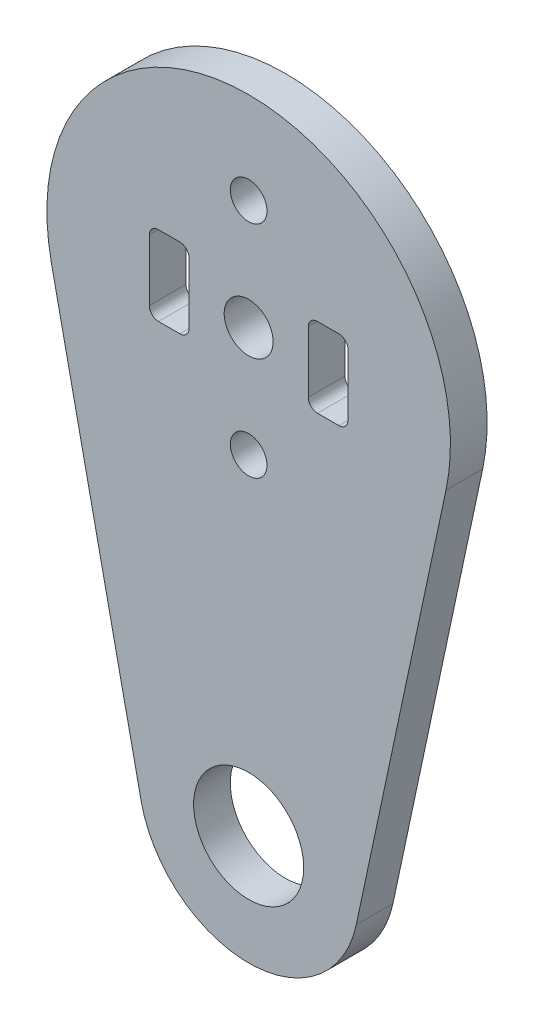
SolidWorks part; units mm, degrees
ref_plane "Alzado" through (0, 0, 0) normal (0, 0, 1) x (1, 0, 0)
ref_plane "Planta" through (0, 0, 0) normal (0, 1, 0) x (1, 0, 0)
ref_plane "Vista lateral" through (0, 0, 0) normal (1, 0, 0) x (0, 0, -1)
sketch "Model" plane through (0, 0, 0) normal (0, 0, 1) x (1, 0, 0)
  line L0 (223.1228, 245.202) -> (221.3728, 245.202)
  line L1 (223.8728, 239.452) -> (223.8728, 244.452)
  line L2 (221.3728, 238.702) -> (223.1228, 238.702)
  line L3 (220.6228, 244.452) -> (220.6228, 239.452)
  line L4 (208.3728, 245.202) -> (210.1228, 245.202)
  line L5 (207.6228, 239.452) -> (207.6228, 244.452)
  line L6 (210.1228, 238.702) -> (208.3728, 238.702)
  line L7 (210.8728, 244.452) -> (210.8728, 239.452)
  line L8 (206.9453, 204.077) -> (199.6099, 238.5145)
  line L9 (231.8858, 238.5145) -> (224.5503, 204.077)
  circle A0 centre (215.7478, 241.952) radius 2
  circle A1 centre (215.7478, 232.952) radius 1.5
  circle A2 centre (215.7478, 250.952) radius 1.5
  arc A3 (221.3728, 245.202) -> (220.6228, 244.452) centre (221.3728, 244.452) ccw
  arc A4 (223.8728, 244.452) -> (223.1228, 245.202) centre (223.1228, 244.452) ccw
  arc A5 (223.1228, 238.702) -> (223.8728, 239.452) centre (223.1228, 239.452) ccw
  arc A6 (220.6228, 239.452) -> (221.3728, 238.702) centre (221.3728, 239.452) ccw
  arc A7 (210.8728, 244.452) -> (210.1228, 245.202) centre (210.1228, 244.452) ccw
  arc A8 (208.3728, 245.202) -> (207.6228, 244.452) centre (208.3728, 244.452) ccw
  arc A9 (207.6228, 239.452) -> (208.3728, 238.702) centre (208.3728, 239.452) ccw
  arc A10 (210.1228, 238.702) -> (210.8728, 239.452) centre (210.1228, 239.452) ccw
  circle A11 centre (215.7478, 205.952) radius 4.5
  arc A12 (206.9453, 204.077) -> (224.5503, 204.077) centre (215.7478, 205.952) ccw
  arc A13 (231.8858, 238.5145) -> (199.6099, 238.5145) centre (215.7478, 241.952) ccw
extrude "Saliente-Extruir1" add sketch "Model" along normal blind 3
